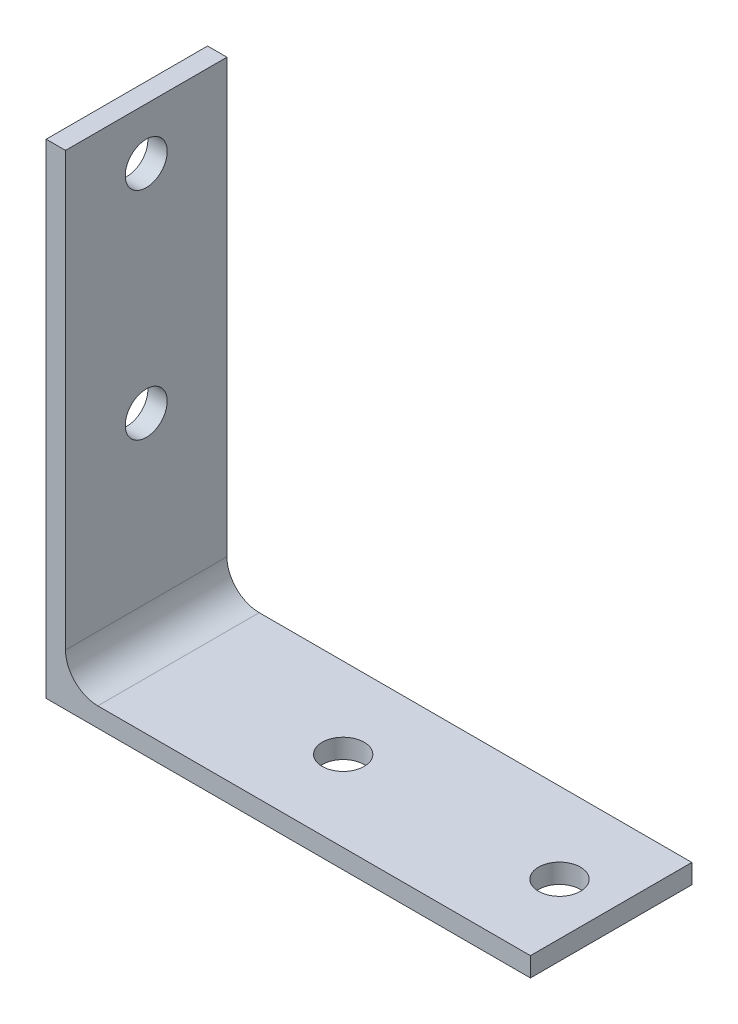
SolidWorks part; units mm, degrees
ref_plane "Front Plane" through (0, 0, 0) normal (0, 0, 1) x (1, 0, 0)
ref_plane "Top Plane" through (0, 0, 0) normal (0, 1, 0) x (1, 0, 0)
ref_plane "Right Plane" through (0, 0, 0) normal (1, 0, 0) x (0, 0, -1)
sketch "Sketch1" plane through (0, 0, 0) normal (0, 0, 1) x (1, 0, 0)
  line L1 (0, 0) -> (38.1, 0)
  line L2 (0, 0) -> (0, 38.1)
  line L3 (0, 38.1) -> (1.524, 38.1)
  line L4 (38.1, 0) -> (38.1, 1.524)
  line L5 (38.1, 0) -> (38.1, 38.1) construction
  line L6 (1.524, 1.524) -> (36.576, 1.524)
  line L7 (1.524, 1.524) -> (1.524, 36.576)
  line L8 (1.524, 36.576) -> (1.524, 38.1)
  line L9 (36.576, 1.524) -> (38.1, 1.524)
  line L10 (0, 38.1) -> (38.1, 38.1) construction
  line L11 (1.524, 36.576) -> (36.576, 36.576) construction
  line L12 (36.576, 1.524) -> (36.576, 36.576) construction
  dimension "D1" = 38.1
  dimension "D2" = 38.1
  dimension "D3" = 1.524
extrude "Boss-Extrude1" add sketch "Sketch1" along normal mid plane 12.7
fillet "Fillet1" radius 2.54 1 edges at (1.524, 1.524, 0)
sketch "Sketch2" plane through (1.524, 0, 0) normal (1, 0, 0) x (0, 0, -1)
  line L0 (6.35, 4.064) -> (6.35, 38.1) construction
  line L2 (0, 4.064) -> (0, 38.1) construction
  line L3 (-6.35, 4.064) -> (6.35, 4.064) construction
  line L4 (-6.35, 38.1) -> (6.35, 38.1) construction
  line L7 (-6.35, 34.036) -> (6.35, 34.036) construction
  line L8 (-6.35, 4.064) -> (-6.35, 38.1) construction
  circle A0 centre (0, 34.036) radius 1.651
  circle A1 centre (0, 17.018) radius 1.651
  dimension "D1" = 3.302
  dimension "D3" = 3.302
  dimension "D2" = 17.018
  dimension "D4" = 17.018
extrude "Cut-Extrude1" cut sketch "Sketch2" against normal through all
sketch "Sketch3" plane through (0, 1.524, 0) normal (0, 1, 0) x (1, 0, 0)
  line L0 (4.064, 0) -> (38.1, 0) construction
  line L1 (4.064, 6.35) -> (4.064, -6.35) construction
  line L2 (38.1, -6.35) -> (38.1, 6.35) construction
  line L3 (0, -6.35) -> (0, 6.35) construction
  circle A0 centre (17.018, 0) radius 1.651
  circle A1 centre (34.036, 0) radius 1.651
  dimension "D1" = 3.302
  dimension "D2" = 3.302
  dimension "D3" = 17.018
  dimension "D4" = 17.018
extrude "Cut-Extrude2" cut sketch "Sketch3" against normal through all
